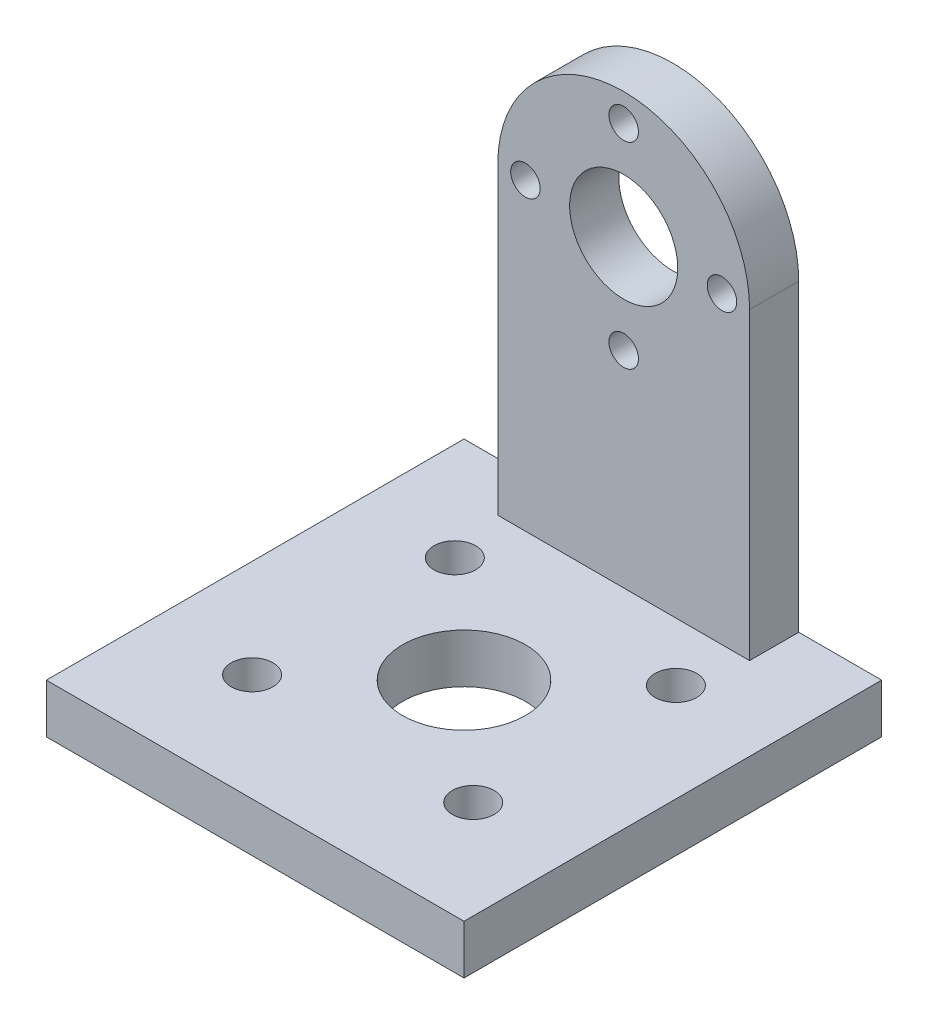
SolidWorks part; units mm, degrees
ref_plane "Front Plane" through (0, 0, 0) normal (0, 0, 1) x (1, 0, 0)
ref_plane "Top Plane" through (0, 0, 0) normal (0, 1, 0) x (1, 0, 0)
ref_plane "Right Plane" through (0, 0, 0) normal (1, 0, 0) x (0, 0, -1)
sketch "Sketch1" plane through (0, 0, 0) normal (0, 0, 1) x (1, 0, 0)
  line L0 (0, 0) -> (0, -68) construction
  line L1 (10.25, 0) -> (10.25, -68)
  line L2 (-10.25, 0) -> (-10.25, -68)
  line L3 (0, 0) -> (0, -68) construction
  line L4 (17, 0) -> (17, -68)
  line L5 (-17, 0) -> (-17, -68)
  line L7 (-10.25, -68) -> (10.25, -68)
  line L8 (-10.25, -68) -> (-10.25, -32.75)
  line L9 (-10.25, -32.75) -> (10.25, -32.75)
  line L10 (10.25, -68) -> (10.25, -32.75)
  line L11 (-17, -32.75) -> (17, -32.75)
  line L12 (-17, -32.75) -> (-17, -28.75)
  line L13 (-17, -28.75) -> (17, -28.75)
  line L14 (17, -32.75) -> (17, -28.75)
  line L15 (-10.25, -68) -> (10.25, -68)
  line L16 (-10.25, -68) -> (-10.25, -79.25)
  line L17 (-10.25, -79.25) -> (10.25, -79.25)
  line L18 (10.25, -68) -> (10.25, -79.25)
  arc A0 (10.25, 0) -> (-10.25, 0) centre (0, 0) ccw
  arc A1 (-10.25, -68) -> (10.25, -68) centre (0, -68) ccw
  arc A2 (17, 0) -> (-17, 0) centre (0, 0) ccw
  arc A3 (-17, -68) -> (17, -68) centre (0, -68) ccw
  circle A4 centre (0, 0) radius 8
  circle A5 centre (0, 8) radius 1.2
  circle A6 centre (8, 0) radius 1.2
  circle A7 centre (0, -8) radius 1.2
  circle A8 centre (-8, 0) radius 1.2
  circle A9 centre (0, -68) radius 10.25
  circle A10 centre (0, 0) radius 4.4
  point P3 (0, -34)
  point P10 (0, -34)
  point P28 (0, 0)
  dimension "D2" = 10.25
  dimension "D3" = 17
  dimension "D4" = 16
  dimension "D5" = 2.4
  dimension "D10" = 8.8
  dimension "D1" = 68
  dimension "D7" = 35.25
  dimension "D8" = 4
  dimension "D9" = 11.25
  dimension "D6" = 4
extrude "Boss-Extrude1" add sketch "Sketch1" along normal blind 4 contours A8 A4 A7 A6 A5 A10 | L1 A0 L2 L13 A8 A4 A5 A6 A7
sketch "Sketch3" plane through (0, -28.75, 0) normal (0, -1, 0) x (-1, 0, 0)
  line L21 (-10.25, -4) -> (-10.25, 0) construction
  line L22 (-17, 0) -> (17, 0)
  line L23 (-17, 0) -> (-17, -34)
  line L24 (-17, -34) -> (17, -34)
  line L25 (17, 0) -> (17, -34)
  circle A0 centre (0, -17) radius 5
  circle A1 centre (-9, -8.75) radius 1.7
  circle A2 centre (9, -8.75) radius 1.7
  circle A3 centre (9, -25.25) radius 1.7
  circle A4 centre (-9, -25.25) radius 1.7
  dimension "D3" = 3.4
  dimension "D4" = 8.25
  dimension "D5" = 9
  dimension "D8" = 17
  dimension "D10" = 9
  dimension "D11" = 8.25
  dimension "D1" = 34
  dimension "D2" = 6.75
  dimension "D9" = 34
  dimension "D6" = 2
  dimension "D7" = 2
extrude "Boss-Extrude3" add sketch "Sketch3" against normal blind 4
